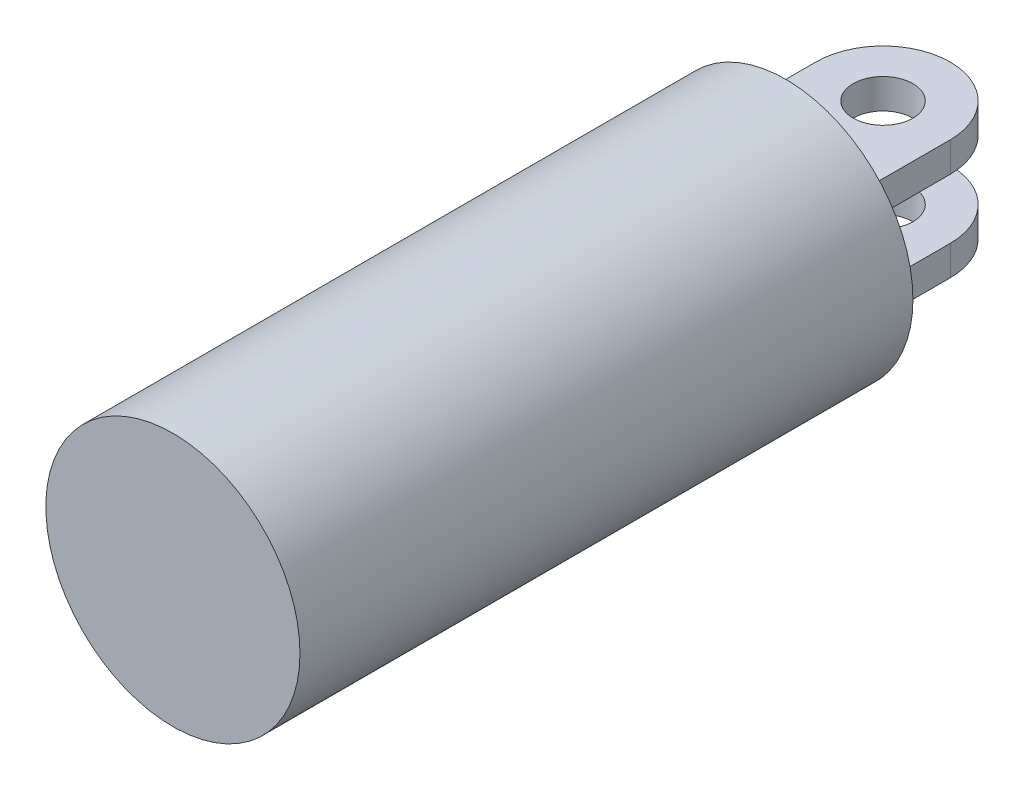
SolidWorks part; units mm, degrees
ref_plane "Front" through (0, 0, 0) normal (0, 0, 1) x (1, 0, 0)
ref_plane "Top" through (0, 0, 0) normal (0, 1, 0) x (1, 0, 0)
ref_plane "Right" through (0, 0, 0) normal (1, 0, 0) x (0, 0, -1)
sketch "Sketch1" plane through (0, 0, 0) normal (0, 0, 1) x (1, 0, 0)
  circle A0 centre (0, 0) radius 53.975
  dimension "D1" = 107.95
extrude "Extrude1" add sketch "Sketch1" along normal blind 260.35
sketch "Sketch2" plane through (0, 0, 0) normal (1, 0, 0) x (0, -1, 0)
  line L0 (-25.4, 0) -> (-25.4, 69.85)
  line L1 (-25.4, 0) -> (-12.7, 0)
  line L2 (53.975, 0) -> (-53.975, 0) construction
  line L3 (-25.4, 69.85) -> (-12.7, 69.85)
  line L4 (-12.7, 69.85) -> (-12.7, 0)
  line L5 (12.7, 0) -> (25.4, 0)
  line L6 (12.7, 0) -> (12.7, 69.85)
  line L7 (12.7, 69.85) -> (25.4, 69.85)
  line L8 (25.4, 69.85) -> (25.4, 0)
  line L9 (12.7, 0) -> (-12.7, 0) construction
  dimension "D1" = 25.4
  dimension "D2" = 12.7
  dimension "D4" = 69.85
extrude "Extrude2" add sketch "Sketch2" along normal mid plane 57.15
sketch "Sketch3" plane through (0, 25.4, 0) normal (0, 1, 0) x (-1, 0, 0)
  line L0 (-28.575, -69.85) -> (-28.575, 0) construction
  line L1 (-28.575, -69.85) -> (28.575, -69.85) construction
  line L2 (0, 55) -> (0, -55) construction
  line L3 (28.575, -69.85) -> (28.575, 0) construction
  line L4 (-28.575, -41.275) -> (-28.575, -85.725)
  line L5 (-28.575, -85.725) -> (28.575, -85.725)
  line L6 (28.575, -85.725) -> (28.575, -41.275)
  circle A0 centre (0, -41.275) radius 12.7
  arc A1 (-28.575, -41.275) -> (28.575, -41.275) centre (0, -41.275) ccw
  dimension "D1" = 25.4
  dimension "D2" = 28.575
extrude "Cut-Extrude1" cut sketch "Sketch3" against normal through all
